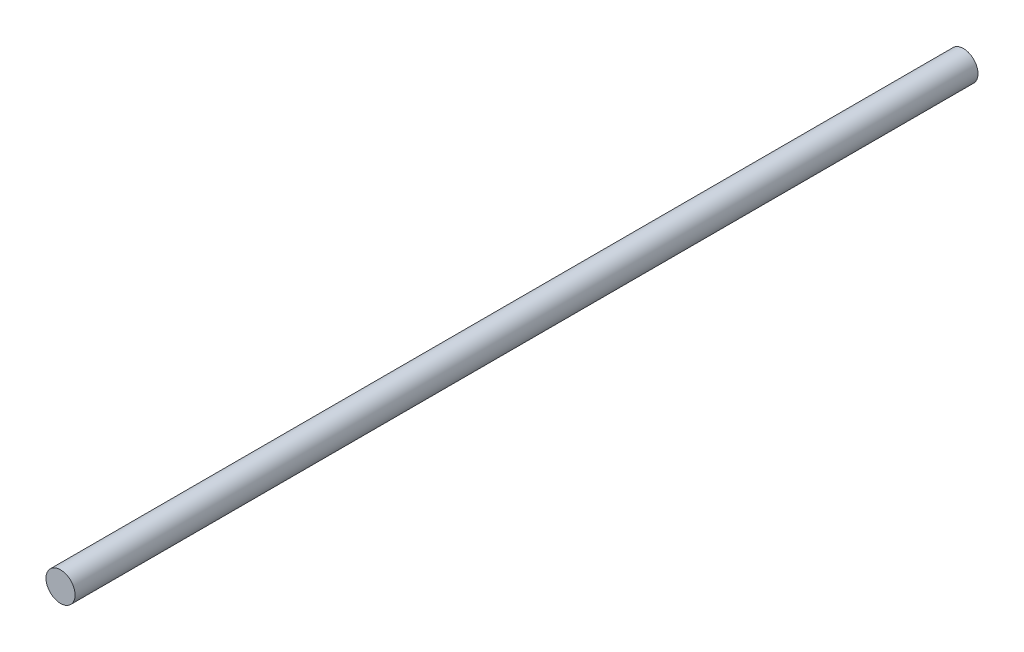
SolidWorks part; units mm, degrees
ref_plane "Plan de face" through (0, 0, 0) normal (0, 0, 1) x (1, 0, 0)
ref_plane "Plan de dessus" through (0, 0, 0) normal (0, 1, 0) x (1, 0, 0)
ref_plane "Plan de droite" through (0, 0, 0) normal (1, 0, 0) x (0, 0, -1)
sketch "Esquisse2" plane through (0, 0, 0) normal (0, 0, 1) x (1, 0, 0)
  circle A0 centre (0, 0) radius 5
  dimension "D1" = 10
extrude "Boss.-Extru.3" add sketch "Esquisse2" along normal blind 310
